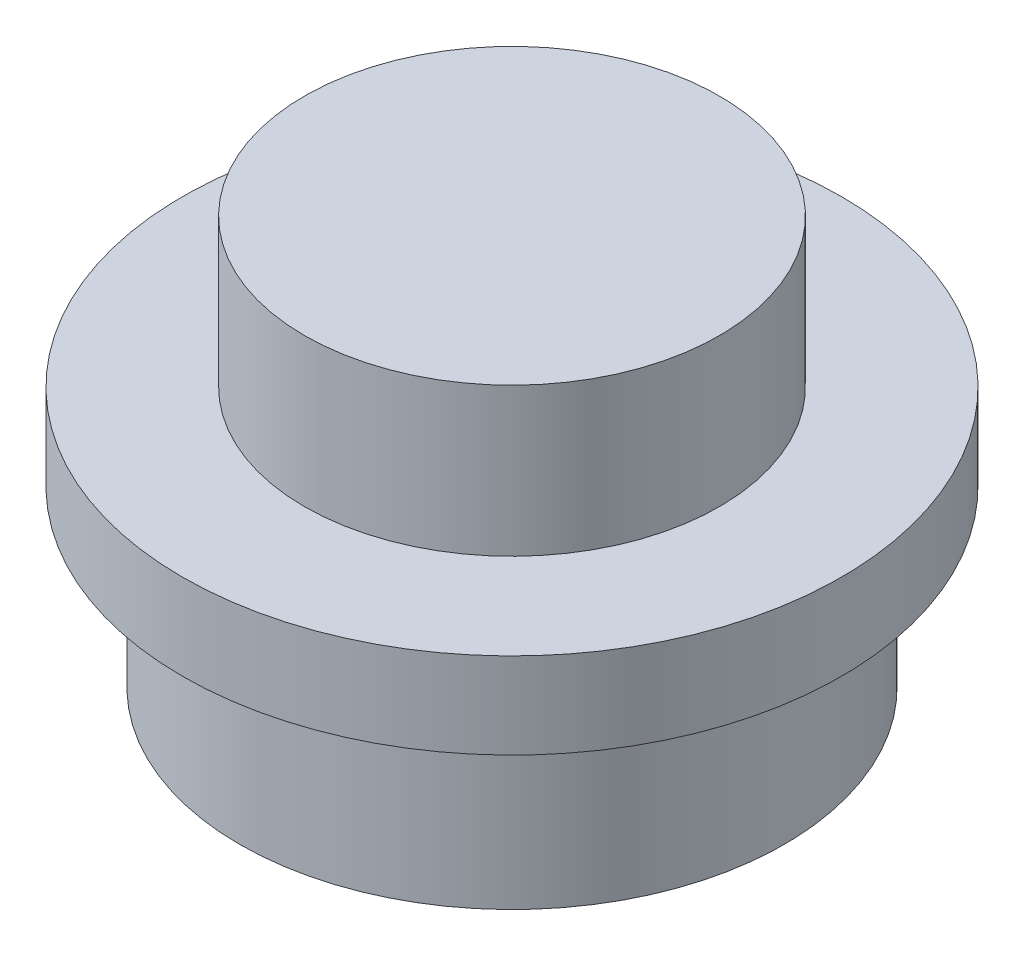
SolidWorks part; units mm, degrees
ref_plane "Front Plane" through (0, 0, 0) normal (0, 0, 1) x (1, 0, 0)
ref_plane "Top Plane" through (0, 0, 0) normal (0, 1, 0) x (1, 0, 0)
ref_plane "Right Plane" through (0, 0, 0) normal (1, 0, 0) x (0, 0, -1)
sketch "Sketch5" plane through (0, 0, 0) normal (0, 0, 1) x (1, 0, 0)
  line L0 (0, 3.0615) -> (0, -2.9385) construction
  line L1 (0, 2.78) -> (2.465, 2.78)
  line L2 (2.465, 2.78) -> (2.465, 1.02)
  line L3 (2.465, 1.02) -> (3.915, 1.02)
  line L4 (3.915, 1.02) -> (3.915, 0)
  line L5 (3.915, 0) -> (3.235, 0)
  line L6 (3.235, 0) -> (3.235, -2.07)
  line L7 (3.235, -2.07) -> (2.445, -2.07)
  line L8 (2.445, -2.07) -> (2.445, 0)
  line L9 (2.445, 0) -> (1.345, 0)
  line L10 (1.345, 0) -> (1.345, 1.8)
  line L11 (1.345, 1.8) -> (0, 1.8)
  line L12 (0, 2.78) -> (0, 1.8)
  point P9 (0, 0)
  point P16 (0, 0)
  dimension "D1" = 0.98
  dimension "D2" = 2.465
  dimension "D3" = 1.76
  dimension "D4" = 1.45
  dimension "D5" = 1.02
  dimension "D6" = 0.68
  dimension "D7" = 2.07
  dimension "D8" = 0.79
  dimension "D9" = 1.1
  dimension "D10" = 1.8
revolve "Revolve1" add sketch "Sketch5" angle 360 about L0
